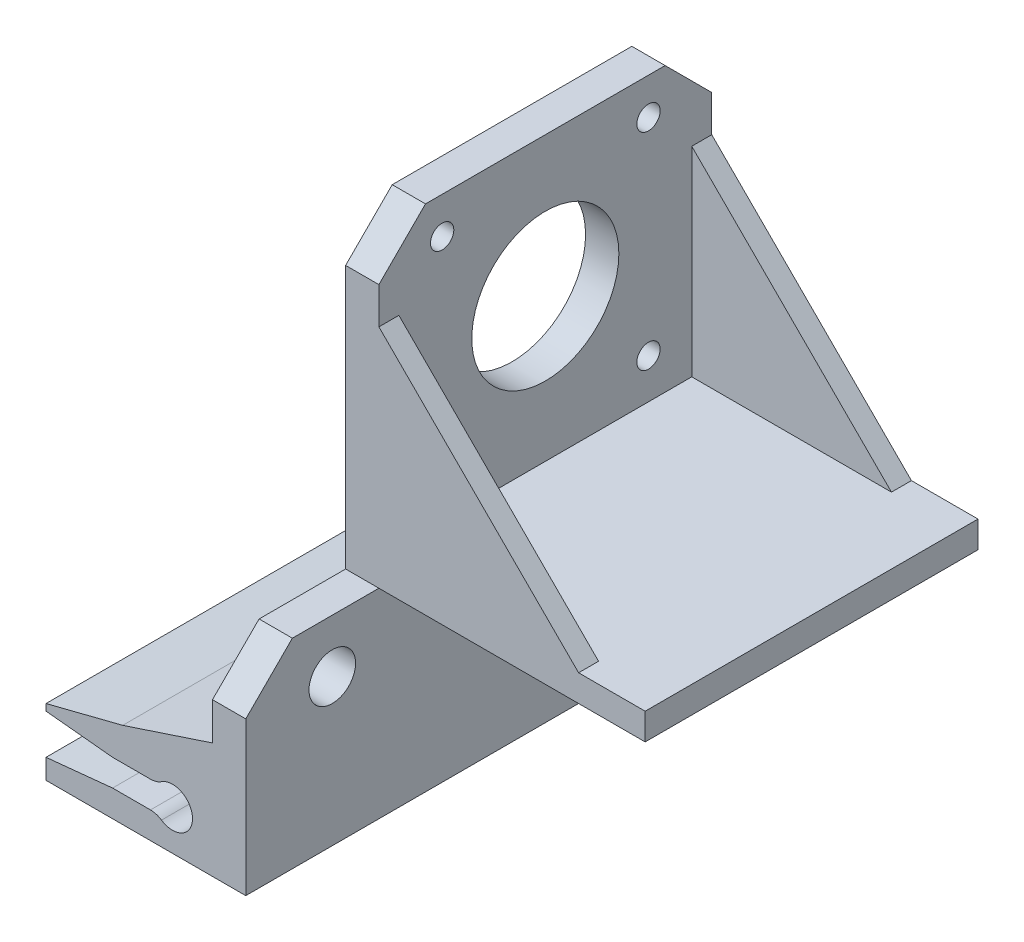
SolidWorks part; units mm, degrees
ref_plane "Front Plane" through (0, 0, 0) normal (0, 0, 1) x (1, 0, 0)
ref_plane "Top Plane" through (0, 0, 0) normal (0, 1, 0) x (1, 0, 0)
ref_plane "Right Plane" through (0, 0, 0) normal (1, 0, 0) x (0, 0, -1)
sketch "Sketch1" plane through (0, 0, 0) normal (1, 0, 0) x (0, 0, -1)
  line L0 (-35.6897, 15.5) -> (55, 15.5) construction
  line L1 (-25, -25.5) -> (25, -25.5)
  line L2 (-25, -25.5) -> (-25, 21)
  line L3 (-25, 21) -> (25, 21)
  line L4 (25, -25.5) -> (25, 21)
  line L5 (15.5, 28.4138) -> (15.5, -31.069) construction
  line L6 (-43.7931, 0) -> (63.4483, 0) construction
  line L7 (0, 38.1897) -> (0, -41.6379) construction
  circle A0 centre (15.5, 15.5) radius 1.75
  circle A2 centre (15.5, -15.5) radius 1.75
  circle A3 centre (-15.5, -15.5) radius 1.75
  circle A4 centre (-15.5, 15.5) radius 1.75
  dimension "D7" = 3.5
  dimension "D1" = 50
  dimension "D2" = 5.5
  dimension "D3" = 9.5
  dimension "D4" = 46.5
  dimension "D5" = 21
  dimension "D6" = 25
extrude "Boss-Extrude1" add sketch "Sketch1" along normal blind 5
sketch "Sketch2" plane through (5, 0, 0) normal (1, 0, 0) x (0, 0, -1)
  circle A0 centre (0, 0) radius 11.05
  dimension "D1" = 22.1
extrude "Cut-Extrude1" cut sketch "Sketch2" against normal blind 5
sketch "Sketch3" plane through (5, 0, 0) normal (1, 0, 0) x (0, 0, -1)
  line L1 (-25, -25.5) -> (25, -25.5)
  line L2 (-25, -25.5) -> (-25, -21.5)
  line L3 (-25, -21.5) -> (25, -21.5)
  line L4 (25, -25.5) -> (25, -21.5)
  dimension "D1" = 4
extrude "Boss-Extrude2" add sketch "Sketch3" along normal blind 40
sketch "Sketch4" plane through (0, 0, -25) normal (0, 0, -1) x (-1, 0, 0)
  line L0 (-45, -21.5) -> (-5, -21.5) construction
  line L1 (-35, -21.5) -> (-5, 8.5)
  line L2 (-5, -21.5) -> (-5, 21) construction
  dimension "D1" = 30
  dimension "D2" = 30
rib "Rib1" sketch "Sketch4" sketch "Sketch4" thickness 3 extrusion direction parallel to sketch draft on no parameters "D1"=3
mirror "Mirror1" about plane through (0, 0, 0) normal (0, 0, 1) of "Rib1"
sketch "Sketch5" plane through (0, -25.5, 0) normal (0, -1, 0) x (1, 0, 0)
  line L0 (0, -55) -> (0, 55) construction
  line L1 (0, -25) -> (5, -25)
  line L2 (0, -25) -> (0, 25)
  line L3 (0, 25) -> (5, 25)
  line L4 (5, -25) -> (5, 25)
  line L5 (45, -25) -> (0, -25) construction
  line L6 (45, 25) -> (0, 25) construction
  dimension "D1" = 5
extrude "Boss-Extrude3" add sketch "Sketch5" along normal blind 27
sketch "Sketch8" plane through (0, 0, 25) normal (0, 0, 1) x (1, 0, 0)
  line L0 (0, -55) -> (0, 55) construction
  line L1 (5, -52.5) -> (0, -52.5)
  line L2 (5, -52.5) -> (5, -25.5)
  line L3 (5, -25.5) -> (0, -25.5)
  line L4 (0, -52.5) -> (0, -25.5)
  dimension "D1" = 27
extrude "Boss-Extrude5" add sketch "Sketch8" along normal blind 20
mirror "Mirror2" about plane through (0, 0, 0) normal (0, 0, 1) of "Boss-Extrude5"
sketch "Sketch9" plane through (0, -52.5, 0) normal (0, -1, 0) x (1, 0, 0)
  line L0 (0, -55) -> (0, 55) construction
  line L1 (5, 45) -> (0, 45)
  line L2 (5, 45) -> (5, -45)
  line L3 (5, -45) -> (0, -45)
  line L4 (0, 45) -> (0, -45)
  line L5 (0, -45) -> (5, -45) construction
extrude "Boss-Extrude6" add sketch "Sketch9" along normal blind 3
sketch "Sketch10" plane through (0, 0, -45) normal (0, 0, -1) x (-1, 0, 0)
  line L0 (25.0094, -46.5) -> (25.0094, -45.5024)
  line L5 (0, -38.1313) -> (0, -45.5)
  line L8 (15.0094, -46.1023) -> (15.0094, -52.8159) construction
  line L15 (0, 55) -> (0, -55) construction
  line L18 (0, -55.5) -> (25.0094, -55.5)
  line L21 (15.0094, -51.5) -> (25.0094, -52.5)
  line L22 (0, -55.5) -> (0, -45.5)
  line L24 (25.0094, -55.5) -> (25.0094, -52.5)
  line L25 (0, -55.5) -> (-5, -55.5) construction
  line L26 (9.3166, -51.5) -> (15.0094, -51.5)
  line L27 (9.3166, -47.5) -> (15.0094, -47.5)
  line L28 (0, -38.1313) -> (13.4891, -42.584)
  line L29 (0, -25.5) -> (0, -55.5) construction
  line L30 (13.4891, -42.584) -> (25.0094, -45.5024)
  line L31 (15.0094, -47.5) -> (25.0094, -46.5)
  arc A4 (7.6583, -47) -> (7.6583, -52) centre (6, -49.5) ccw
  arc A5 (9.3166, -51.5) -> (7.6583, -52) centre (9.3166, -54.5) ccw
  arc A6 (9.3166, -47.5) -> (7.6583, -47) centre (9.3166, -44.5) cw
  point P11 (25.0094, -51.5)
  point P13 (25.0094, -47.5)
  dimension "D5" = 4
  dimension "D6" = 1
  dimension "D7" = 6
  dimension "D8" = 3
  dimension "D1" = 10
  dimension "D2" = 10
  dimension "D3" = 6
  dimension "D4" = 10
  dimension "D9" = 10
  dimension "D10" = 1
extrude "Boss-Extrude7" add sketch "Sketch10" against normal up to surface (90 mm away) contours L22 L5 L28 L30 L0 L31 L27 A6 A4 A5 L26 L21 L24 L18 up to face at (2.5, -40.5, 45)
sketch "Sketch12" plane through (0, 0, 0) normal (-1, 0, 0) x (0, 0, 1)
  line L1 (-45, -25.5) -> (-25, -25.5) construction
  line L3 (-45, -25.5) -> (-45, -38.1313) construction
  circle A0 centre (-32, -33.5) radius 3.5
  dimension "D1" = 7
  dimension "D2" = 8
  dimension "D3" = 13
extrude "Cut-Extrude2" cut sketch "Sketch12" against normal through all
mirror "Mirror3" about plane through (0, 0, 0) normal (0, 0, 1) of "Cut-Extrude2"
chamfer "Chamfer1" distance 7 angle 45 1 edges at (2.5, 21, -25)
chamfer "Chamfer2" distance 7 angle 45 3 edges at (2.5, -25.5, -45) (2.5, -25.5, 45) (2.5, 21, 25)
